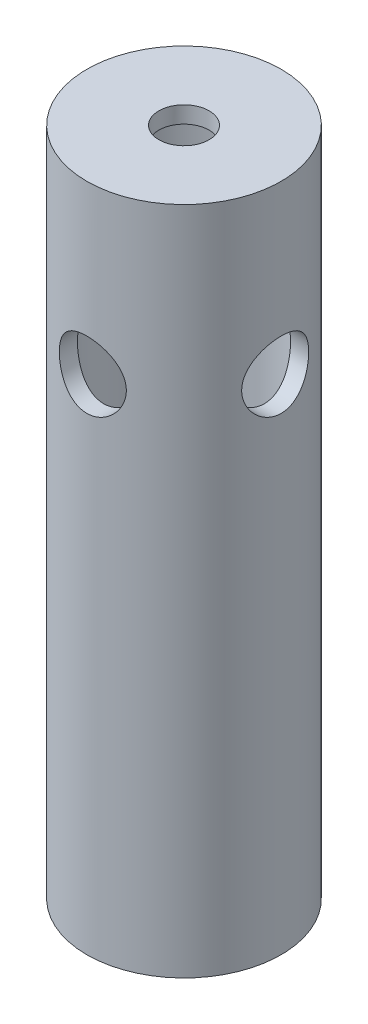
SolidWorks part; units mm, degrees
material "Copper"
ref_plane "Front Plane" through (0, 0, 0) normal (0, 0, 1) x (1, 0, 0)
ref_plane "Top Plane" through (0, 0, 0) normal (0, 1, 0) x (1, 0, 0)
ref_plane "Right Plane" through (0, 0, 0) normal (1, 0, 0) x (0, 0, -1)
sketch "Sketch1" plane through (0, 0, 0) normal (0, 1, 0) x (1, 0, 0)
  circle A0 centre (0, 0) radius 5.8
  dimension "D1" = 11.6
extrude "Boss-Extrude1" add sketch "Sketch1" along normal blind 40
sketch "Sketch3" plane through (0, 0, 0) normal (0, -1, 0) x (1, 0, 0)
  circle A0 centre (0, 0) radius 4.8
  dimension "D1" = 9.6
extrude "Cut-Extrude1" cut sketch "Sketch3" against normal blind 39 contours A0
sketch "Sketch6" plane through (0, 0, 0) normal (0, 0, 1) x (1, 0, 0)
  circle A0 centre (0, 30) radius 2
  dimension "D1" = 4
  dimension "D2" = 30
extrude "Cut-Extrude3" cut sketch "Sketch6" against normal through all
pattern_circular "CirPattern1" count 4 over 360 about axis through (0, 40, 0) along (0, -1, 0) of "Cut-Extrude3"
sketch "Sketch7" plane through (0, 40, 0) normal (0, 1, 0) x (1, 0, 0)
  circle A0 centre (0, 0) radius 1.5
  dimension "D1" = 3
extrude "Cut-Extrude4" cut sketch "Sketch7" against normal up to next
